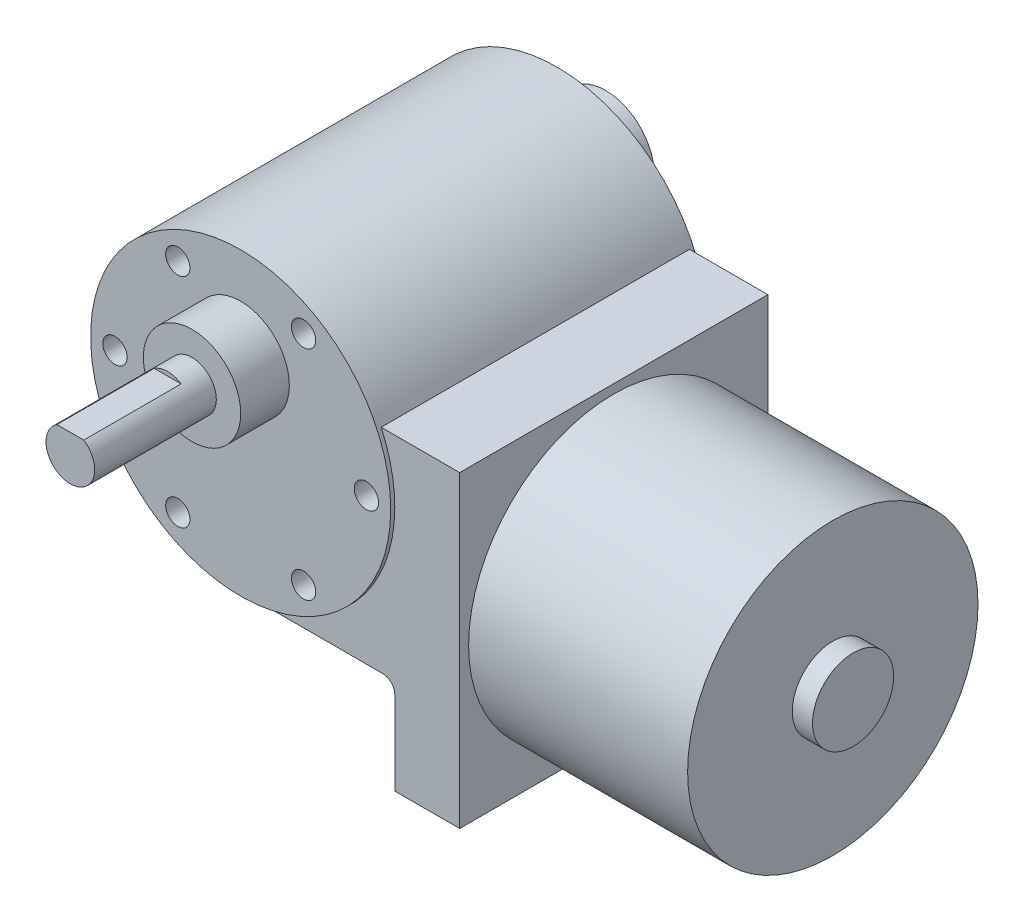
SolidWorks part; units mm, degrees
ref_plane "正面" through (0, 0, 0) normal (0, 0, 1) x (1, 0, 0)
ref_plane "平面" through (0, 0, 0) normal (0, 1, 0) x (1, 0, 0)
ref_plane "右側面" through (0, 0, 0) normal (1, 0, 0) x (0, 0, -1)
sketch "ｽｹｯﾁ1" plane through (0, 0, 0) normal (0, 0, 1) x (1, 0, 0)
  circle A0 centre (0, 0) radius 6
  dimension "D1" = 12
extrude "ﾎﾞｽ - 押し出し1" add sketch "ｽｹｯﾁ1" along normal blind 6
sketch "ｽｹｯﾁ2" plane through (0, 0, 6) normal (0, 0, 1) x (1, 0, 0)
  circle A0 centre (0, 0) radius 3
  dimension "D1" = 6
extrude "ﾎﾞｽ - 押し出し2" add sketch "ｽｹｯﾁ2" along normal blind 15
sketch "ｽｹｯﾁ4" plane through (0, 0, 21) normal (0, 0, 1) x (1, 0, 0)
  line L0 (-1.6583, 2.5) -> (1.6583, 2.5)
  circle A0 centre (0, 0) radius 3 construction
  arc A2 (-1.6583, 2.5) -> (1.6583, 2.5) centre (0, 0) ccw
  point P1 (1.6583, 2.5)
  dimension "D1" = 2.5
extrude "ｶｯﾄ - 押し出し1" cut sketch "ｽｹｯﾁ4" against normal blind 12 flip side to cut
sketch "ｽｹｯﾁ5" plane through (0, 0, 0) normal (0, 0, 1) x (1, 0, 0)
  circle A0 centre (0, -7) radius 18.5
  point P3 (0, 0)
  dimension "D1" = 37
  dimension "D2" = 7
extrude "ﾎﾞｽ - 押し出し3" add sketch "ｽｹｯﾁ5" against normal blind 39 contours A0
sketch "ｽｹｯﾁ6" plane through (0, 0, -39) normal (0, 0, -1) x (-1, 0, 0)
  circle A0 centre (0, 0) radius 6
  dimension "D1" = 12
extrude "ﾎﾞｽ - 押し出し4" add sketch "ｽｹｯﾁ6" along normal blind 6
ref_plane "平面1" through (26.5, 0, 0) normal (1, 0, 0) x (0, 0, -1)
sketch "ｽｹｯﾁ7" plane through (26.5, 0, 0) normal (1, 0, 0) x (0, 0, -1)
  line L0 (0, -7) -> (39, -7) construction
  line L1 (0.5, -37.3) -> (38.5, -37.3)
  line L2 (0.5, -37.3) -> (0.5, 0.7)
  line L3 (0.5, 0.7) -> (38.5, 0.7)
  line L4 (38.5, -37.3) -> (38.5, 0.7)
  line L5 (0.5, -37.3) -> (38.5, 0.7) construction
  line L6 (0.5, 0.7) -> (38.5, -37.3) construction
  line L7 (0, 11.5) -> (0, -25.5) construction
  line L8 (39, -25.5) -> (39, 11.5) construction
  point P0 (19.5, -18.3)
  point P11 (19.5, -7)
  dimension "D1" = 38
  dimension "D2" = 11.3
extrude "ﾎﾞｽ - 押し出し5" add sketch "ｽｹｯﾁ7" against normal blind 8 separate body
sketch "ｽｹｯﾁ8" plane through (18.5, 0, 0) normal (-1, 0, 0) x (0, 0, 1)
  line L0 (-0.5, 0.7) -> (-0.5, -37.3) construction
  line L1 (-38.5, 0.7) -> (-0.5, 0.7)
  line L2 (-38.5, 0.7) -> (-38.5, -25.5)
  line L3 (-38.5, -25.5) -> (-0.5, -25.5)
  line L4 (-0.5, 0.7) -> (-0.5, -25.5)
  line L5 (-38.5, 0.7) -> (-0.5, -25.5) construction
  line L6 (-38.5, -25.5) -> (-0.5, 0.7) construction
  line L7 (-39, -25.5) -> (0, -25.5) construction
  point P4 (-19.5, -12.4)
extrude "ﾎﾞｽ - 押し出し6" add sketch "ｽｹｯﾁ8" along normal up to next
sketch "ｽｹｯﾁ9" plane through (26.5, 0, 0) normal (1, 0, 0) x (0, 0, -1)
  line L0 (0.5, 0.7) -> (38.5, -37.3) construction
  line L1 (0.5, -37.3) -> (38.5, 0.7) construction
  circle A0 centre (19.5, -18.3) radius 17.9
  dimension "D1" = 35.8
extrude "ﾎﾞｽ - 押し出し7" add sketch "ｽｹｯﾁ9" along normal blind 27
sketch "ｽｹｯﾁ10" plane through (53.5, 0, 0) normal (1, 0, 0) x (0, 0, -1)
  circle A0 centre (19.5, -18.3) radius 5
  dimension "D1" = 10
extrude "ﾎﾞｽ - 押し出し8" add sketch "ｽｹｯﾁ10" along normal blind 2.5
sketch "ｽｹｯﾁ11" plane through (0, 0, 0) normal (0, 0, 1) x (1, 0, 0)
  circle A0 centre (0, -7) radius 15.5 construction
  circle A1 centre (0, -7) radius 18.5 construction
  circle A2 centre (-15.5, -7) radius 1.5
  circle A3 centre (-7.75, 6.4234) radius 1.5
  circle A4 centre (7.75, 6.4234) radius 1.5
  circle A5 centre (15.5, -7) radius 1.5
  circle A6 centre (7.75, -20.4234) radius 1.5
  circle A7 centre (-7.75, -20.4234) radius 1.5
  point P6 (0, 0)
  point P7 (0, 0)
  point P18 (0, -7)
  point P19 (0, 0)
  point P20 (0, 0)
  point P21 (0, 0)
  point P22 (0, 0)
  dimension "D1" = 31
  dimension "D2" = 3
  dimension "D3" = 6
extrude "ｶｯﾄ - 押し出し2" cut sketch "ｽｹｯﾁ11" against normal blind 4
fillet "ﾌｨﾚｯﾄ1" radius 1.5 1 edges at (18.5, -25.5, -19.5)
